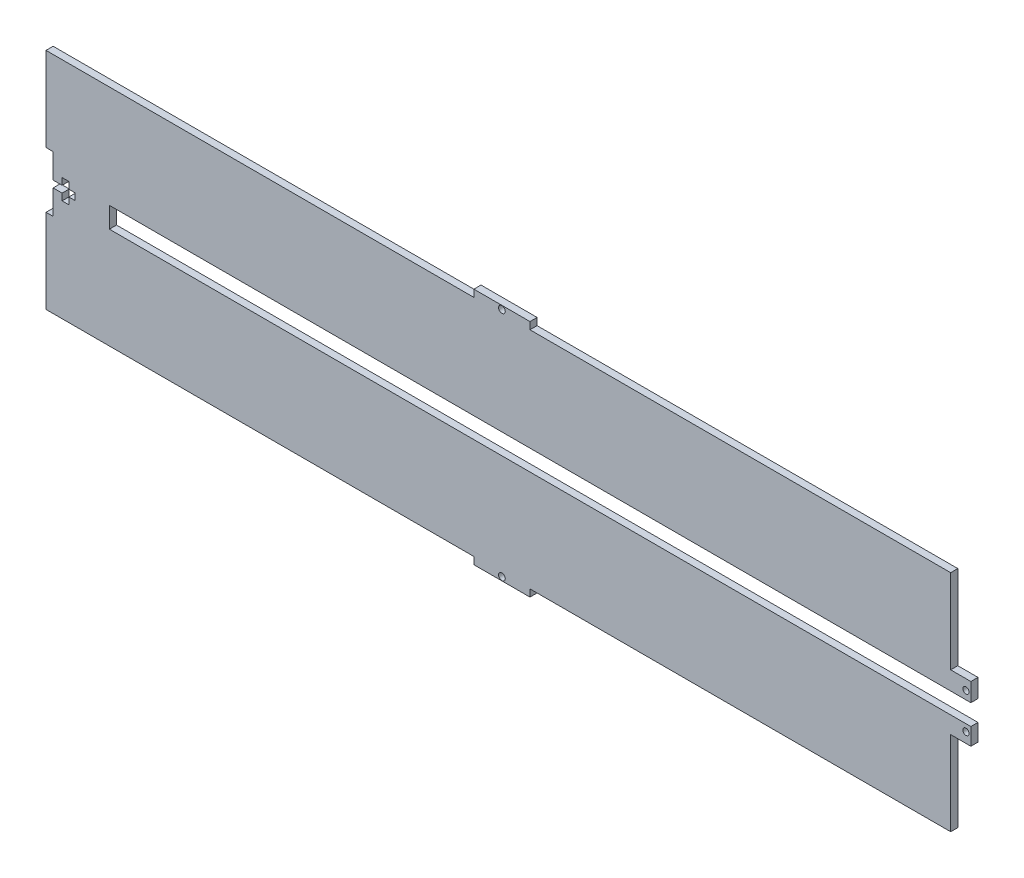
SolidWorks part; units mm, degrees
ref_plane "Front Plane" through (0, 0, 0) normal (0, 0, 1) x (1, 0, 0)
ref_plane "Top Plane" through (0, 0, 0) normal (0, 1, 0) x (1, 0, 0)
ref_plane "Right Plane" through (0, 0, 0) normal (1, 0, 0) x (0, 0, -1)
sketch "Sketch1" plane through (0, 0, 0) normal (0, 0, 1) x (1, 0, 0)
  line L5 (-201.59, 50) -> (201.59, -50) construction
  line L6 (201.59, 50) -> (-201.59, -50) construction
  line L11 (-201.59, 50) -> (-201.59, 12.5)
  line L12 (-188.59, 0) -> (210.59, 0) construction
  line L25 (-198.41, -1.5) -> (-198.41, -12.5)
  line L26 (-198.41, 12.5) -> (-201.59, 12.5)
  line L44 (-198.41, 12.5) -> (-198.41, 1.5)
  line L45 (-198.41, -12.5) -> (-201.59, -12.5)
  line L47 (-198.41, 12.5) -> (-201.59, -12.5) construction
  line L48 (-198.41, -12.5) -> (-201.59, 12.5) construction
  line L66 (-188.59, 1.5) -> (-191.41, 1.5)
  line L67 (-188.59, 1.5) -> (-188.59, -1.5)
  line L68 (-188.59, -1.5) -> (-191.41, -1.5)
  line L76 (-194.41, 4.5) -> (-191.41, 4.5)
  line L77 (-194.41, 4.5) -> (-194.41, 1.5)
  line L78 (-194.41, -4.5) -> (-191.41, -4.5)
  line L79 (-191.41, 4.5) -> (-191.41, 1.5)
  line L80 (-194.41, 1.5) -> (-198.41, 1.5)
  line L81 (-191.41, -1.5) -> (-191.41, -4.5)
  line L82 (-194.41, -1.5) -> (-194.41, -4.5)
  line L87 (-194.41, -1.5) -> (-198.41, -1.5)
  line L99 (-201.59, -12.5) -> (-201.59, -50)
  line L101 (-201.59, 50) -> (-10.91, 50)
  line L106 (-201.59, -50) -> (-10.91, -50)
  line L107 (1.59, -53.18) -> (1.59, -50) construction
  line L118 (201.59, -50) -> (201.59, -12.5)
  line L120 (210.59, 0) -> (201.59, 0) construction
  line L121 (210.59, -12.5) -> (201.59, -12.5)
  line L122 (210.59, -12.5) -> (210.59, 12.5)
  line L123 (210.59, 12.5) -> (201.59, 12.5)
  line L125 (210.59, -12.5) -> (201.59, 12.5) construction
  line L126 (210.59, 12.5) -> (201.59, -12.5) construction
  line L127 (201.59, 12.5) -> (201.59, 50)
  line L128 (-10.91, 53.18) -> (14.09, 53.18)
  line L130 (-10.91, 53.18) -> (-10.91, 50)
  line L131 (-198.41, -12.5) -> (-198.41, -50) construction
  line L137 (14.09, 53.18) -> (14.09, 50)
  line L138 (-10.91, 53.18) -> (14.09, 50) construction
  line L139 (-10.91, 50) -> (14.09, 53.18) construction
  line L140 (-10.91, -53.18) -> (14.09, -53.18)
  line L141 (-10.91, -53.18) -> (-10.91, -50)
  line L143 (14.09, -53.18) -> (14.09, -50)
  line L144 (-10.91, -53.18) -> (14.09, -50) construction
  line L145 (-10.91, -50) -> (14.09, -53.18) construction
  line L146 (1.59, 53.18) -> (1.59, 50) construction
  line L147 (1.59, -50) -> (1.59, 50) construction
  line L148 (14.09, 50) -> (201.59, 50)
  line L149 (14.09, -50) -> (201.59, -50)
  line L150 (206.09, 12.5) -> (206.09, -12.5) construction
  line L152 (208.39, 8) -> (208.39, 12.5) construction
  circle A4 centre (1.59, 51.59) radius 1.5
  circle A5 centre (1.59, -51.59) radius 1.5
  circle A6 centre (208.39, 8) radius 1.4
  circle A9 centre (208.39, -8) radius 1.4
  point P0 (0, 0)
  point P6 (1.59, 51.59)
  point P7 (0, 0)
  point P8 (-200, 0)
  point P13 (-295.09, 0)
  point P18 (-292.635, -0.75)
  point P19 (-294.5, 0)
  point P27 (303.18, 0)
  point P28 (206.09, 0)
  point P42 (1.59, -51.59)
  dimension "D5" = 13
  dimension "D12" = 3.18
  dimension "D14" = 25
  dimension "D17" = 3
  dimension "D18" = 3
  dimension "D20" = 2.8
  dimension "D22" = 8
  dimension "D23" = 8
  dimension "D25" = 2.8
  dimension "D2" = 100
  dimension "D3" = 25
  dimension "D4" = 3
  dimension "D6" = 4
  dimension "D7" = 3
  dimension "D8" = 3.18
  dimension "D9" = 9
  dimension "D10" = 25
  dimension "D11" = 25
  dimension "D13" = 400
  dimension "D15" = 9
  dimension "D16" = 3.18
  dimension "D19" = 1.59
  dimension "D21" = 2.3
  dimension "D24" = 2.3
extrude "Boss-Extrude1" add sketch "Sketch1" along normal blind 3.18
sketch "Sketch2" plane through (0, 0, 3.18) normal (0, 0, 1) x (1, 0, 0)
  line L0 (201.59, 12.5) -> (201.59, 4.65) construction
  line L1 (-173.3475, 4.3103) -> (152.8045, 4.3103)
  line L2 (-173.3475, 4.3103) -> (-173.3475, -4.8897)
  line L3 (-173.3475, -4.8897) -> (196.6525, -4.8897)
  line L5 (-173.3475, 4.3103) -> (196.6525, -4.8897) construction
  line L6 (-173.3475, -4.8897) -> (152.8045, 4.3103) construction
  line L7 (196.6525, -4.8897) -> (201.37, -4.8897)
  line L9 (152.8045, 4.3103) -> (201.59, 4.3103)
  line L12 (201.37, -4.8897) -> (212.0876, -4.8897)
  line L14 (201.59, 4.3103) -> (212.0876, 4.3103)
  line L15 (212.0876, -4.8897) -> (212.0876, 4.3103)
  point P0 (0, 0)
  point P12 (0, 0)
  dimension "D1" = 9.2
  dimension "D2" = 370
extrude "Cut-Extrude1" cut sketch "Sketch2" against normal blind 10
